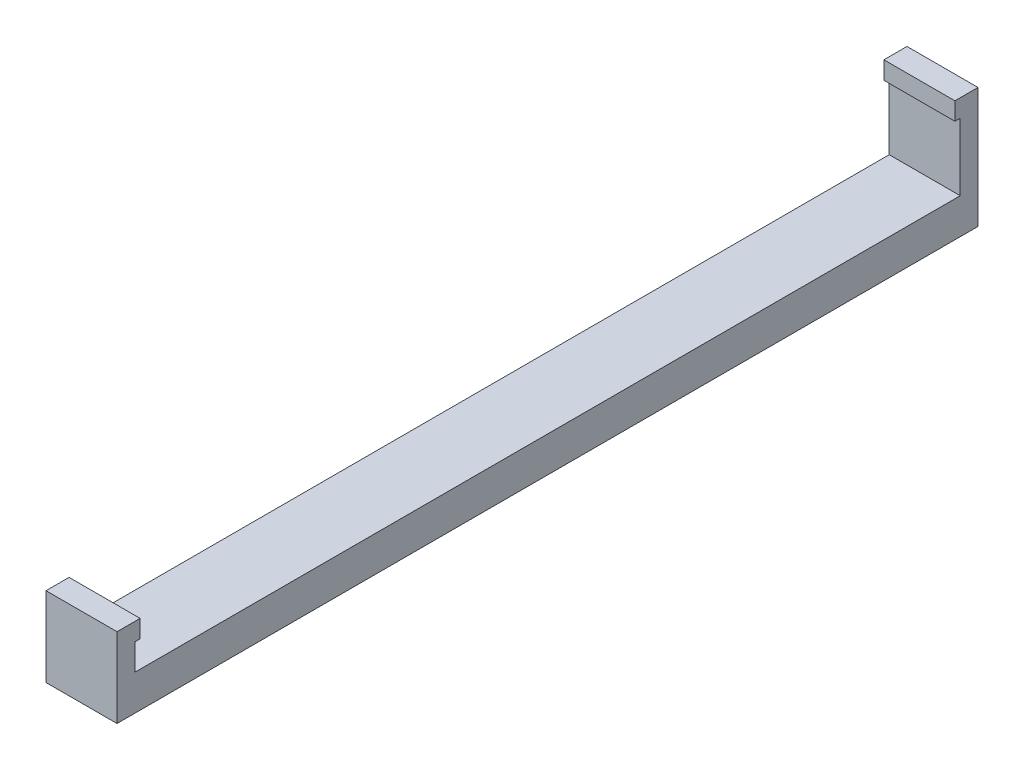
SolidWorks part; units mm, degrees
ref_plane "Front Plane" through (0, 0, 0) normal (0, 0, 1) x (1, 0, 0)
ref_plane "Top Plane" through (0, 0, 0) normal (0, 1, 0) x (1, 0, 0)
ref_plane "Right Plane" through (0, 0, 0) normal (1, 0, 0) x (0, 0, -1)
sketch "Sketch1" plane through (0, 0, 0) normal (0, 1, 0) x (1, 0, 0)
  line L2 (0, 0) -> (0, 116.22)
  line L4 (10, 0) -> (10, 116.22)
  line L5 (0, 0) -> (10, 116.22) construction
  line L6 (0, 116.22) -> (10, 0) construction
  line L7 (0, 116.22) -> (10, 116.22)
  line L13 (0, 0) -> (10, 0)
  point P4 (5, 58.11)
  dimension "D1" = 116.22
  dimension "D2" = 10
extrude "Boss-Extrude1" add sketch "Sketch1" along normal blind 5
sketch "Sketch3" plane through (10, 0, 0) normal (1, 0, 0) x (0, 0, -1)
  line L0 (0.75, 8.7) -> (0, 8.7)
  line L1 (0, 0) -> (-2.5, 0)
  line L2 (0, 0) -> (0, 8.7)
  line L4 (-2.5, 0) -> (-2.5, 8.7)
  line L5 (0, 0) -> (-2.5, 8.7) construction
  line L6 (0, 8.7) -> (-2.5, 0) construction
  line L7 (116.22, 0) -> (118.72, 0)
  line L8 (116.22, 0) -> (116.22, 14.45)
  line L10 (118.72, 0) -> (118.72, 14.45)
  line L11 (116.22, 0) -> (118.72, 14.45) construction
  line L12 (116.22, 14.45) -> (118.72, 0) construction
  line L14 (-2.5, 8.7) -> (-2.5, 11.2)
  line L15 (-2.5, 11.2) -> (0.75, 11.2)
  line L16 (0.75, 8.7) -> (0.75, 11.2)
  line L17 (-2.5, 8.7) -> (0.75, 11.2) construction
  line L18 (-2.5, 11.2) -> (0.75, 8.7) construction
  line L19 (115.47, 14.45) -> (116.22, 14.45)
  line L21 (118.72, 14.45) -> (118.72, 16.95)
  line L22 (118.72, 16.95) -> (115.47, 16.95)
  line L23 (115.47, 14.45) -> (115.47, 16.95)
  line L24 (118.72, 14.45) -> (115.47, 16.95) construction
  line L25 (118.72, 16.95) -> (115.47, 14.45) construction
  point P4 (-1.25, 4.35)
  point P10 (117.47, 7.225)
  point P15 (-0.875, 9.95)
  point P19 (117.095, 15.7)
  dimension "D1" = 2.5
  dimension "D2" = 2.5
  dimension "D3" = 8.7
  dimension "D4" = 14.45
  dimension "D5" = 2.5
  dimension "D6" = 3.25
  dimension "D7" = 2.5
  dimension "D8" = 3.25
extrude "Boss-Extrude2" add sketch "Sketch3" against normal through all
